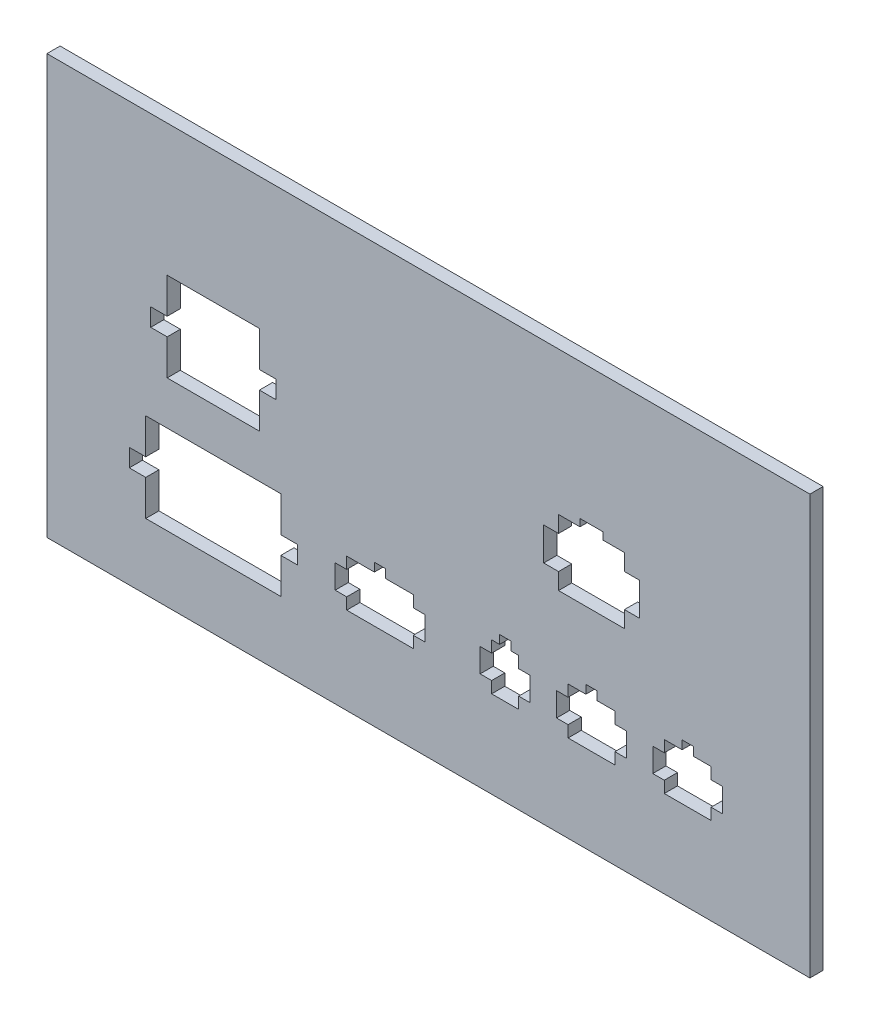
SolidWorks part; units mm, degrees
ref_plane "Front Plane" through (0, 0, 0) normal (0, 0, 1) x (1, 0, 0)
ref_plane "Top Plane" through (0, 0, 0) normal (0, 1, 0) x (1, 0, 0)
ref_plane "Right Plane" through (0, 0, 0) normal (1, 0, 0) x (0, 0, -1)
sketch "Sketch1" plane through (0, 0, 0) normal (0, 0, 1) x (1, 0, 0)
  line L1 (-52.9, -26.8) -> (52.9, -26.8)
  line L2 (-52.9, -26.8) -> (-52.9, 26.8)
  line L3 (-52.9, 26.8) -> (52.9, 26.8)
  line L4 (52.9, -26.8) -> (52.9, 26.8)
  line L5 (-52.9, -26.8) -> (52.9, 26.8) construction
  line L6 (-52.9, 26.8) -> (52.9, -26.8) construction
  point P0 (0, 0)
  dimension "D1" = 105.8
  dimension "D2" = 53.6
extrude "Boss-Extrude1" add sketch "Sketch1" along normal blind 2
sketch "Sketch2" plane through (0, 0, 0) normal (0, 0, 1) x (1, 0, 0)
  line L0 (9.6, -6.5) -> (13.7, -6.5)
  line L1 (-42.9, -3.3) -> (-22.4, -3.3)
  line L2 (-42.9, -3.3) -> (-42.9, -16.8)
  line L3 (-42.9, -16.8) -> (-22.4, -16.8)
  line L4 (-22.4, -3.3) -> (-22.4, -16.8)
  line L5 (19.75, 15.05) -> (29.75, 15.05)
  line L6 (19.75, 15.05) -> (19.75, 5.05)
  line L7 (19.75, 5.05) -> (29.75, 5.05)
  line L8 (29.75, 15.05) -> (29.75, 5.05)
  line L9 (35.8, -6.5) -> (42.9, -6.5)
  line L10 (35.8, -6.5) -> (35.8, -13.6)
  line L11 (35.8, -13.6) -> (42.9, -13.6)
  line L12 (42.9, -6.5) -> (42.9, -13.6)
  line L13 (9.6, -6.5) -> (9.6, -13.6)
  line L14 (9.6, -13.6) -> (13.7, -13.6)
  line L15 (13.7, -6.5) -> (13.7, -13.6)
  line L16 (-39.65, 16.8) -> (-25.65, 16.8)
  line L17 (-39.65, 16.8) -> (-39.65, 3.3)
  line L18 (-39.65, 3.3) -> (-25.65, 3.3)
  line L19 (-25.65, 16.8) -> (-25.65, 3.3)
  line L20 (21.2, -6.5) -> (28.3, -6.5)
  line L21 (21.2, -6.5) -> (21.2, -13.6)
  line L22 (21.2, -13.6) -> (28.3, -13.6)
  line L23 (28.3, -6.5) -> (28.3, -13.6)
  line L24 (-12.4, -6.5) -> (-2.3, -6.5)
  line L25 (-12.4, -6.5) -> (-12.4, -13.6)
  line L26 (-12.4, -13.6) -> (-2.3, -13.6)
  line L27 (-2.3, -6.5) -> (-2.3, -13.6)
  line L28 (-22.4, -10.05) -> (-12.4, -10.05) construction
  line L29 (13.7, -10.05) -> (21.2, -10.05) construction
  line L30 (28.3, -10.05) -> (35.8, -10.05) construction
  line L31 (-25.65, 10.05) -> (19.75, 10.05) construction
  line L32 (-32.65, -3.3) -> (-32.65, 3.3) construction
  line L33 (-2.3, -10.05) -> (9.6, -10.05) construction
  line L34 (24.75, -6.5) -> (24.75, 5.05) construction
  line L35 (-52.9, 26.8) -> (-52.9, -26.8) construction
  line L36 (52.9, -26.8) -> (52.9, 26.8) construction
  line L37 (52.9, 26.8) -> (-52.9, 26.8) construction
  line L38 (-52.9, -26.8) -> (52.9, -26.8) construction
  line L39 (-39.65, 3.3) -> (-25.65, 16.8) construction
  line L40 (-22.4, -3.3) -> (-42.9, -16.8) construction
  line L41 (-12.4, -13.6) -> (-2.3, -6.5) construction
  line L42 (9.6, -13.6) -> (13.7, -6.5) construction
  line L43 (21.2, -13.6) -> (28.3, -6.5) construction
  line L44 (35.8, -13.6) -> (42.9, -6.5) construction
  line L45 (19.75, 5.05) -> (29.75, 15.05) construction
  dimension "D1" = 20.5
  dimension "D2" = 13.5
  dimension "D3" = 10
  dimension "D4" = 10
  dimension "D5" = 7.1
  dimension "D6" = 7.1
  dimension "D7" = 4.1
  dimension "D8" = 7.1
  dimension "D9" = 14
  dimension "D10" = 13.5
  dimension "D11" = 7.1
  dimension "D12" = 7.1
  dimension "D13" = 10.1
  dimension "D14" = 7.1
  dimension "D15" = 7.5
  dimension "D16" = 10
  dimension "D17" = 10
  dimension "D18" = 10
  dimension "D19" = 10
  dimension "D20" = 10
extrude "Cut-Extrude2" cut sketch "Sketch2" along normal through all
sketch "Sketch4" plane through (0, 0, 2) normal (0, 0, 1) x (1, 0, 0)
  line L0 (-22.4, -3.3) -> (-42.9, -16.8) construction
  line L1 (-45.4, -8.7) -> (-19.9, -8.7)
  line L2 (-45.4, -8.7) -> (-45.4, -11.4)
  line L3 (-45.4, -11.4) -> (-19.9, -11.4)
  line L4 (-19.9, -8.7) -> (-19.9, -11.4)
  line L5 (-45.4, -8.7) -> (-19.9, -11.4) construction
  line L6 (-45.4, -11.4) -> (-19.9, -8.7) construction
  line L7 (-39.65, 3.3) -> (-25.65, 16.8) construction
  line L8 (-42.15, 11.4) -> (-23.15, 11.4)
  line L9 (-42.15, 11.4) -> (-42.15, 8.7)
  line L10 (-42.15, 8.7) -> (-23.15, 8.7)
  line L11 (-23.15, 11.4) -> (-23.15, 8.7)
  line L12 (-42.15, 11.4) -> (-23.15, 8.7) construction
  line L13 (-42.15, 8.7) -> (-23.15, 11.4) construction
  line L14 (19.75, 5.05) -> (29.75, 5.05) construction
  line L15 (23, 5.05) -> (26.5, 5.05)
  line L16 (23, 5.05) -> (23, 16.15)
  line L17 (23, 16.15) -> (26.5, 16.15)
  line L18 (26.5, 5.05) -> (26.5, 16.15)
  line L19 (24.75, 16.15) -> (24.75, 10.05) construction
  line L20 (19.75, 5.05) -> (29.75, 15.05) construction
  line L21 (9.6, -13.6) -> (13.7, -13.6) construction
  line L22 (17.5, 12.55) -> (32, 12.55)
  line L23 (17.5, 12.55) -> (17.5, 7.55)
  line L24 (17.5, 7.55) -> (32, 7.55)
  line L25 (32, 12.55) -> (32, 7.55)
  line L26 (17.5, 12.55) -> (32, 7.55) construction
  line L27 (17.5, 7.55) -> (32, 12.55) construction
  line L28 (10.8, -13.6) -> (12.5, -13.6)
  line L29 (10.8, -13.6) -> (10.8, -5.2)
  line L30 (10.8, -5.2) -> (12.5, -5.2)
  line L31 (12.5, -13.6) -> (12.5, -5.2)
  line L32 (21.2, -13.6) -> (28.3, -13.6) construction
  line L33 (23.9, -13.6) -> (25.6, -13.6)
  line L34 (23.9, -13.6) -> (23.9, -5.2)
  line L35 (23.9, -5.2) -> (25.6, -5.2)
  line L36 (25.6, -13.6) -> (25.6, -5.2)
  line L37 (35.8, -13.6) -> (42.9, -13.6) construction
  line L38 (38.5, -13.6) -> (40.2, -13.6)
  line L39 (38.5, -13.6) -> (38.5, -5.2)
  line L40 (38.5, -5.2) -> (40.2, -5.2)
  line L41 (40.2, -13.6) -> (40.2, -5.2)
  line L42 (11.65, -10.05) -> (11.65, -5.2) construction
  line L43 (9.6, -13.6) -> (13.7, -6.5) construction
  line L44 (-12.4, -13.6) -> (-2.3, -13.6) construction
  line L45 (21.2, -13.6) -> (28.3, -6.5) construction
  line L46 (24.75, -10.05) -> (24.75, -5.2) construction
  line L47 (-8.2, -13.6) -> (-6.5, -13.6)
  line L48 (35.8, -13.6) -> (42.9, -6.5) construction
  line L49 (39.35, -10.05) -> (39.35, -5.2) construction
  line L50 (-8.2, -13.6) -> (-8.2, -5.2)
  line L51 (-8.2, -5.2) -> (-6.5, -5.2)
  line L52 (-6.5, -13.6) -> (-6.5, -5.2)
  line L53 (-7.35, -10.05) -> (-7.35, -5.2) construction
  line L54 (-12.4, -13.6) -> (-2.3, -6.5) construction
  line L55 (-6.5, -5.2) -> (10.8, -5.2) construction
  line L56 (25.6, -5.2) -> (38.5, -5.2) construction
  line L57 (12.5, -5.2) -> (23.9, -5.2) construction
  line L58 (-0.55, -10.05) -> (-2.3, -10.05) construction
  line L59 (-14.15, -8.25) -> (-0.55, -8.25)
  line L60 (-14.15, -8.25) -> (-14.15, -11.85)
  line L61 (-14.15, -11.85) -> (-0.55, -11.85)
  line L62 (-0.55, -8.25) -> (-0.55, -11.85)
  line L63 (-14.15, -8.25) -> (-0.55, -11.85) construction
  line L64 (-14.15, -11.85) -> (-0.55, -8.25) construction
  line L65 (15.45, -8.25) -> (7.85, -8.25)
  line L66 (15.45, -8.25) -> (15.45, -11.85)
  line L67 (15.45, -11.85) -> (7.85, -11.85)
  line L68 (7.85, -8.25) -> (7.85, -11.85)
  line L69 (15.45, -8.25) -> (7.85, -11.85) construction
  line L70 (15.45, -11.85) -> (7.85, -8.25) construction
  line L71 (30.05, -8.25) -> (19.45, -8.25)
  line L72 (30.05, -8.25) -> (30.05, -11.85)
  line L73 (30.05, -11.85) -> (19.45, -11.85)
  line L74 (19.45, -8.25) -> (19.45, -11.85)
  line L75 (30.05, -8.25) -> (19.45, -11.85) construction
  line L76 (30.05, -11.85) -> (19.45, -8.25) construction
  line L77 (44.65, -8.25) -> (34.05, -8.25)
  line L78 (44.65, -8.25) -> (44.65, -11.85)
  line L79 (44.65, -11.85) -> (34.05, -11.85)
  line L80 (34.05, -8.25) -> (34.05, -11.85)
  line L81 (44.65, -8.25) -> (34.05, -11.85) construction
  line L82 (44.65, -11.85) -> (34.05, -8.25) construction
  line L83 (-2.3, -6.5) -> (-2.3, -13.6) construction
  line L84 (13.7, -10.05) -> (15.45, -10.05) construction
  line L85 (13.7, -6.5) -> (13.7, -13.6) construction
  line L86 (28.3, -10.05) -> (30.05, -10.05) construction
  line L87 (28.3, -6.5) -> (28.3, -13.6) construction
  line L88 (42.9, -10.05) -> (44.65, -10.05) construction
  line L89 (42.9, -6.5) -> (42.9, -13.6) construction
  line L90 (-2.3, -10.05) -> (9.6, -10.05) construction
  point P0 (-32.65, -10.05)
  point P7 (-32.65, 10.05)
  line M14 (-39.65, 3.3) -> (-39.65, 16.8)
  line M16 (-25.65, 16.8) -> (-25.65, 3.3)
  line M18 (-12.4, -13.6) -> (-12.4, -6.5)
  line M19 (-12.4, -6.5) -> (-2.3, -6.5)
  line M20 (-2.3, -6.5) -> (-2.3, -13.6)
  line M26 (-42.9, -16.8) -> (-42.9, -3.3)
  line M28 (-22.4, -3.3) -> (-22.4, -16.8)
  line M30 (21.2, -13.6) -> (21.2, -6.5)
  line M31 (21.2, -6.5) -> (28.3, -6.5)
  line M32 (28.3, -6.5) -> (28.3, -13.6)
  line M34 (9.6, -13.6) -> (9.6, -6.5)
  line M35 (9.6, -6.5) -> (13.7, -6.5)
  line M36 (13.7, -6.5) -> (13.7, -13.6)
  dimension "D1" = 25.5
  dimension "D2" = 2.7
  dimension "D3" = 2.7
  dimension "D4" = 19
  dimension "D5" = 3.5
  dimension "D6" = 11.1
  dimension "D7" = 14.5
  dimension "D8" = 5
  dimension "D9" = 8.4
  dimension "D10" = 1.7
  dimension "D11" = 10.6
  dimension "D12" = 3.6
extrude "Cut-Extrude5" cut sketch "Sketch4" against normal blind 10 contours L11 L8 L10 M16 | L9 L10 L8 M14 | L2 L3 L1 M26 | L4 L1 L3 M28 | L60 L61 L59 M18 | L62 L59 L61 M20 | L52 L51 L50 M19 | L31 L30 L29 M35 | L67 L66 L65 M36 | L65 L68 L67 M34 | L73 L72 L71 M32 | L71 L74 L73 M30 | L36 L35 L34 M31 | L77 L80 L79 L78 | L39 L40 L41 L38 | L16 L17 L18 L15 | L22 L25 L24 L23
sketch "Sketch5" plane through (0, 0, 0) normal (0, 0, 1) x (1, 0, 0)
  line L0 (-52.9, -26.8) -> (-57.9, -26.8)
  line L1 (-57.9, -26.8) -> (-57.9, 36.8)
  line L2 (-57.9, 36.8) -> (57.9, 36.8)
  line L3 (57.9, 36.8) -> (57.9, -26.8)
  line L4 (57.9, -26.8) -> (52.9, -26.8)
  line L6 (52.9, 26.8) -> (-52.9, 26.8)
  line L7 (52.9, 26.8) -> (52.9, -26.8)
  line L8 (52.9, -26.8) -> (-52.9, -26.8)
  line L9 (-52.9, 26.8) -> (-52.9, -26.8)
  line L10 (52.9, 26.8) -> (-52.9, -26.8) construction
  line L11 (52.9, -26.8) -> (-52.9, 26.8) construction
  point P6 (0, 0)
  dimension "D1" = 115.8
  dimension "D2" = 63.6
extrude "Boss-Extrude2" add sketch "Sketch5" along normal up to surface (2 mm away) contours L9 L6 L7 L4 L3 L2 L1 L0 up to face at (-32.65, -10.05, 2)
